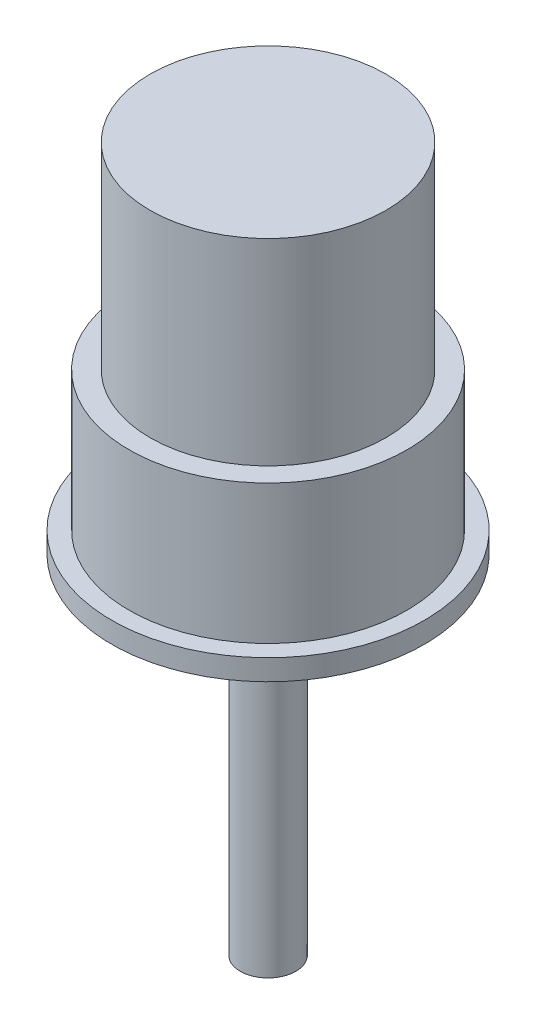
SolidWorks part; units mm, degrees
ref_plane "Front Plane" through (0, 0, 0) normal (0, 0, 1) x (1, 0, 0)
ref_plane "Top Plane" through (0, 0, 0) normal (0, 1, 0) x (1, 0, 0)
ref_plane "Right Plane" through (0, 0, 0) normal (1, 0, 0) x (0, 0, -1)
sketch "Sketch2" plane through (0, 0, 0) normal (0, 0, 1) x (1, 0, 0)
  line L0 (0, 0) -> (0, 29.586) construction
  line L1 (0, 0) -> (-16.9815, 0)
  line L2 (-16.9815, 0) -> (-16.9815, -28.34)
  line L3 (-16.9815, -28.34) -> (-20, -28.34)
  line L4 (-20, -28.34) -> (-20, -48.34)
  line L5 (-20, -48.34) -> (-22.5, -48.34)
  line L6 (-4, -51.34) -> (-4, -101.34)
  line L7 (-4, -101.34) -> (0, -101.34)
  line L8 (-22.5, -48.34) -> (-22.5, -51.34)
  line L9 (-22.5, -51.34) -> (-4, -51.34)
  line L10 (0, 0) -> (0, -101.34)
  dimension "D1" = 16.9815
  dimension "D2" = 28.34
  dimension "D3" = 20
  dimension "D4" = 22.5
  dimension "D5" = 20
  dimension "D6" = 4
  dimension "D7" = 3
  dimension "D8" = 50
revolve "Revolve1" add sketch "Sketch2" angle 360 about L0
equation "\"Stator_OD\"= 68'No Tolerance given"
equation "\"A\"=18.34"
equation "\"Rotor_ID\"= 34'No Tolerance Given"
equation "\"back_bearing_Thickness\"= 20'Currently non-sense"
equation "\"back_bearing_OD\"= 60'currently non-sense"
equation "\"Stator_Gap\"= 0.0375'+- 0.0125 (From 1.3.3.1 Kollmorgen manual)"
equation "\"Back_mount_hole\"= 1.75'To be tapped to M2 (USE LOCKTITE)"
equation "\"facePlate_Mount_Hole\"= 5.75'To be tapped to M6"
equation "\"final_shaftD\"= 8'NEMA 23 shaft diameter. Should fit with harmonic?"
equation "\"back_bearing_ID\"= 40'Random number"
equation "\"D1@Sketch2\" = \"rotor_shaftD\" / 2"
equation "\"rotor_shaftD\"= \"Rotor_ID\" - (0.0185)*2'+-0.0065 (from manual)"
equation "\"D2@Sketch2\"=\"A\"+10"
equation "\"D3@Sketch2\" = \"back_bearing_ID\" / 2"
equation "\"back_bearing_IDOD\"= 45'Random number, OD of the inner bearing ring"
equation "\"D4@Sketch2\" = \"back_bearing_IDOD\" / 2"
equation "\"D5@Sketch2\"=\"back_bearing_Thickness\""
equation "\"D6@Sketch2\"= \"final_shaftD\" / 2"
equation "\"final_shaftL\"= 50'random length. Idk"
equation "\"D8@Sketch2\"=\"final_shaftL\""
